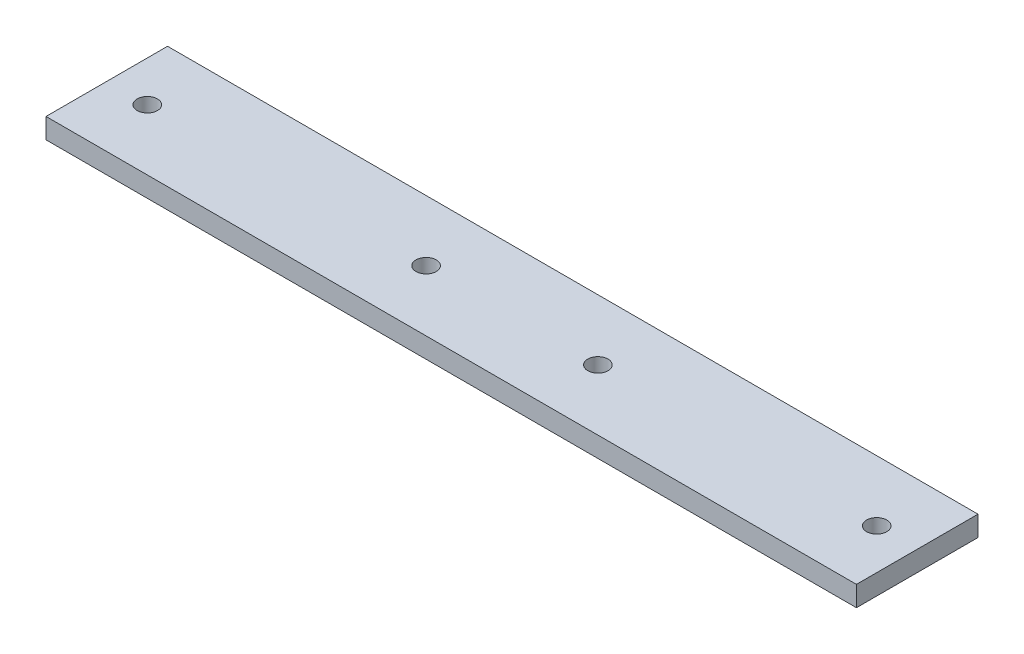
SolidWorks part; units mm, degrees
ref_plane "Front Plane" through (0, 0, 0) normal (0, 0, 1) x (1, 0, 0)
ref_plane "Top Plane" through (0, 0, 0) normal (0, 1, 0) x (1, 0, 0)
ref_plane "Right Plane" through (0, 0, 0) normal (1, 0, 0) x (0, 0, -1)
sketch "Sketch1" plane through (0, 0, 0) normal (0, 1, 0) x (1, 0, 0)
  line L0 (-14, -7.9167) -> (186, -7.9167) construction
  line L1 (-14, 7.0833) -> (186, 7.0833)
  line L2 (-14, 7.0833) -> (-14, -22.9167)
  line L3 (-14, -22.9167) -> (186, -22.9167)
  line L4 (186, 7.0833) -> (186, -22.9167)
  line L5 (86, 7.0833) -> (86, -22.9167) construction
  circle A0 centre (176, -7.9167) radius 2.5
  circle A1 centre (-4, -7.9167) radius 2.5
  circle A2 centre (107.2, -7.9167) radius 2.5
  circle A3 centre (64.8, -7.9167) radius 2.5
  dimension "D3" = 5
  dimension "D5" = 5
  dimension "D1" = 30
  dimension "D2" = 200
  dimension "D4" = 10
  dimension "D6" = 21.2
extrude "Boss-Extrude1" add sketch "Sketch1" along normal blind 5
